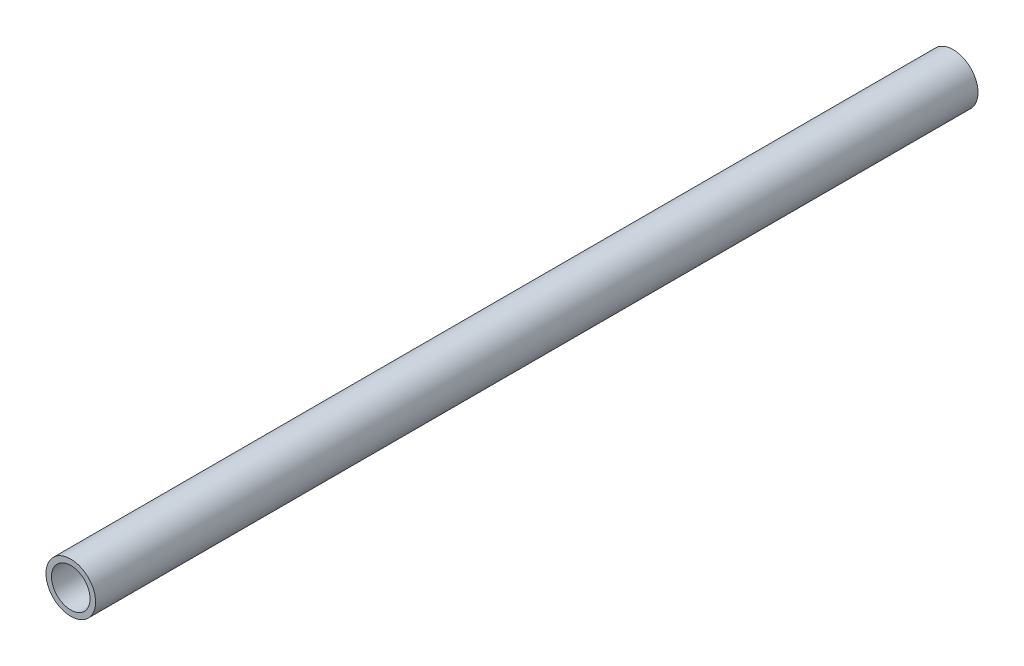
SolidWorks part; units mm, degrees
ref_plane "Front Plane" through (0, 0, 0) normal (0, 0, 1) x (1, 0, 0)
ref_plane "Top Plane" through (0, 0, 0) normal (0, 1, 0) x (1, 0, 0)
ref_plane "Right Plane" through (0, 0, 0) normal (1, 0, 0) x (0, 0, -1)
sketch "Sketch1" plane through (0, 0, 0) normal (0, 0, 1) x (1, 0, 0)
  circle A0 centre (0, 0) radius 9
  circle A1 centre (0, 0) radius 7
  dimension "D1" = 14
  dimension "D2" = 18
extrude "Boss-Extrude1" add sketch "Sketch1" along normal blind 320.02
